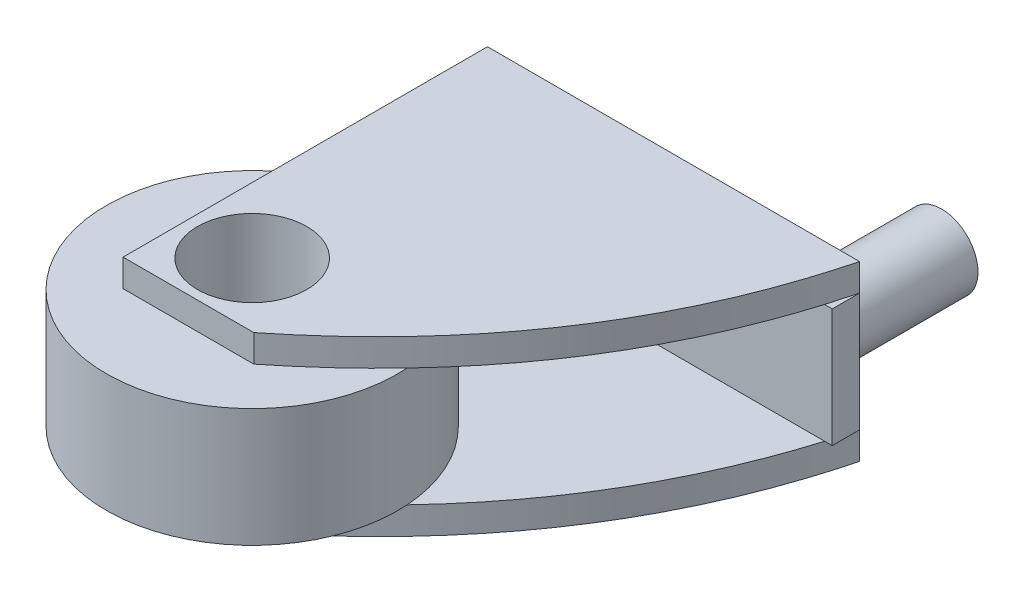
SolidWorks part; units mm, degrees
ref_plane "前视基准面" through (0, 0, 0) normal (0, 0, 1) x (1, 0, 0)
ref_plane "上视基准面" through (0, 0, 0) normal (0, 1, 0) x (1, 0, 0)
ref_plane "右视基准面" through (0, 0, 0) normal (1, 0, 0) x (0, 0, -1)
sketch "草图1" plane through (0, 0, 0) normal (0, 1, 0) x (1, 0, 0)
  circle A0 centre (0, 0) radius 16
  circle A1 centre (0, 0) radius 6
  dimension "D1" = 32
  dimension "D2" = 12
extrude "凸台-拉伸1" add sketch "草图1" along normal blind 13
sketch "草图2" plane through (0, 13, 0) normal (0, 1, 0) x (1, 0, 0)
  line L0 (33.6657, 33) -> (27.5046, 9.1845) construction
  line L1 (-7.1743, -6.9948) -> (7.1743, -6.9948)
  line L2 (-7.1743, -6.9948) -> (-7.1743, 33)
  line L3 (-7.1743, 33) -> (7.1743, 33)
  line L9 (7.1743, 33) -> (33.6657, 33)
  line L13 (27.5046, 9.1845) -> (7.1743, -6.9948) construction
  circle A0 centre (0, 0) radius 16 construction
  spline S0 degree 2 poles (33.6657, 33) (27.5046, 9.1845) (7.1743, -6.9948) knots 0 0 0 1 1 1
  point P4 (0, -6.9948)
  dimension "D1" = 33
extrude "凸台-拉伸2" add sketch "草图2" along normal blind 3
ref_plane "基准面1" through (0, 6.5, 0) normal (0, 1, 0) x (1, 0, 0)
mirror "镜向1" about plane through (0, 6.5, 0) normal (0, 1, 0) of "凸台-拉伸2"
sketch "草图3" plane through (0, 0, -33) normal (0, 0, -1) x (-1, 0, 0)
  line L0 (-33.6657, 0) -> (7.1743, 0) construction
  line L1 (-33.6657, 0) -> (7.1743, 0)
  line L2 (-33.6657, 13) -> (-33.6657, 0)
  line L3 (7.1743, 13) -> (7.1743, 0)
  line L4 (-33.6657, 13) -> (7.1743, 13)
  line L5 (7.1743, 13) -> (7.1743, 16)
  line L6 (7.1743, 16) -> (-33.6657, 16)
  line L7 (-33.6657, 16) -> (-33.6657, 13)
  line L8 (-33.6657, 13) -> (7.1743, 13)
  line L9 (7.1743, 13) -> (7.1743, 16)
  line L10 (7.1743, 16) -> (-33.6657, 16)
  line L11 (-33.6657, 16) -> (-33.6657, 13)
  line M5 (-33.6657, 13) -> (7.1743, 13)
  dimension "D1" = 0
extrude "凸台-拉伸3" add sketch "草图3" against normal blind 3 contours L3 L2 L1 M5
sketch "草图4" plane through (0, 0, -33) normal (0, 0, -1) x (-1, 0, 0)
  line L0 (26.95, 6.5) -> (-26.95, 6.5) construction
  line L1 (-33.6657, 13) -> (-33.6657, 0) construction
  circle A0 centre (-27.6657, 6.5) radius 4
  dimension "D1" = 8
  dimension "D2" = 6
extrude "凸台-拉伸4" add sketch "草图4" along normal blind 15
sketch "草图5" plane through (0, -3, 0) normal (0, -1, 0) x (1, 0, 0)
  circle A1 centre (0, 0) radius 6
  circle A2 centre (0, 0) radius 6
  circle A3 centre (0, 0) radius 16
  circle A4 centre (0, 0) radius 16
  dimension "D1" = 0
  dimension "D2" = 0
extrude "切除-拉伸1" cut sketch "草图5" against normal blind 30 contours A2
